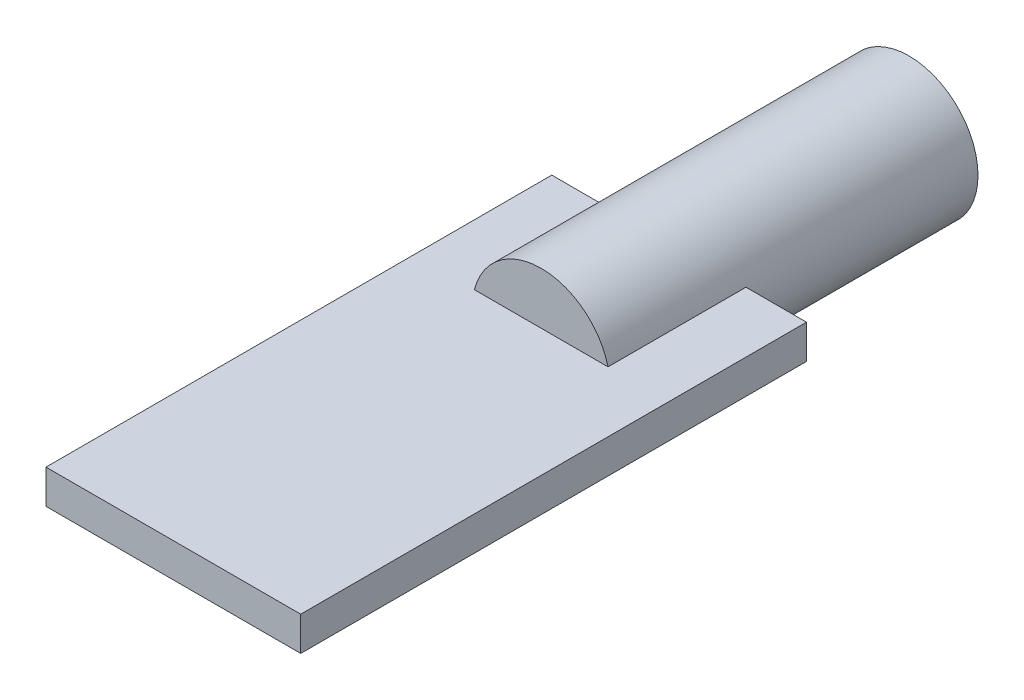
SolidWorks part; units mm, degrees
ref_plane "Front Plane" through (0, 0, 0) normal (0, 0, 1) x (1, 0, 0)
ref_plane "Top Plane" through (0, 0, 0) normal (0, 1, 0) x (1, 0, 0)
ref_plane "Right Plane" through (0, 0, 0) normal (1, 0, 0) x (0, 0, -1)
sketch "Sketch5" plane through (0, 0, 0) normal (0, 0, 1) x (1, 0, 0)
  circle A0 centre (0, 0) radius 7.5
  dimension "D1" = 15
extrude "Boss-Extrude3" add sketch "Sketch5" along normal blind 40
sketch "Sketch10" plane through (0, 0, 40) normal (0, 0, 1) x (1, 0, 0)
  line L1 (-13.85, -1.85) -> (13.85, -1.85)
  line L2 (-13.85, -1.85) -> (-13.85, 1.85)
  line L3 (-13.85, 1.85) -> (13.85, 1.85)
  line L4 (13.85, -1.85) -> (13.85, 1.85)
  line L5 (-13.85, -1.85) -> (13.85, 1.85) construction
  line L6 (-13.85, 1.85) -> (13.85, -1.85) construction
  point P0 (0, 0)
  dimension "D1" = 27.7
  dimension "D2" = 3.7
extrude "Cut-Extrude2" cut sketch "Sketch10" against normal blind 15
sketch "Sketch11" plane through (0, 0, 25) normal (0, 0, 1) x (1, 0, 0)
  line L1 (-13.85, -1.85) -> (13.85, -1.85)
  line L2 (-13.85, -1.85) -> (-13.85, 1.85)
  line L3 (-13.85, 1.85) -> (13.85, 1.85)
  line L4 (13.85, -1.85) -> (13.85, 1.85)
  line L5 (-13.85, -1.85) -> (13.85, 1.85) construction
  line L6 (-13.85, 1.85) -> (13.85, -1.85) construction
  point P0 (0, 0)
  dimension "D1" = 3.7
  dimension "D2" = 27.7
extrude "Boss-Extrude5" add sketch "Sketch11" along normal blind 55
